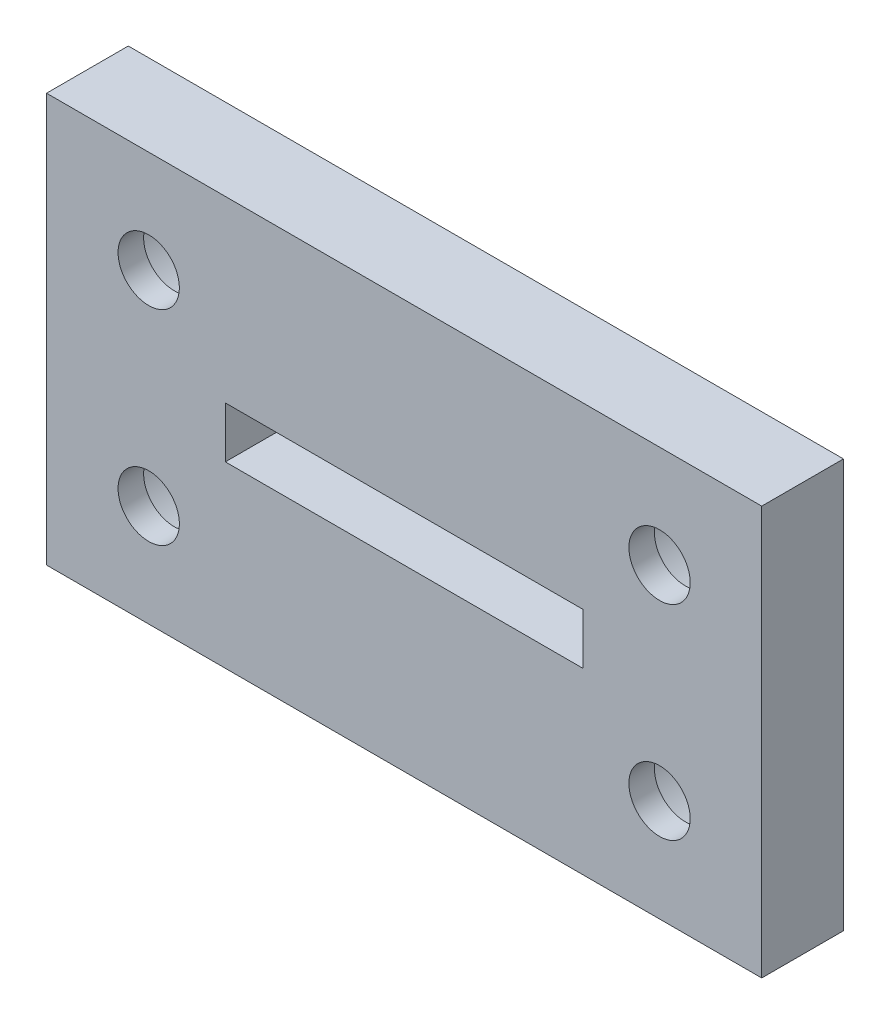
SolidWorks part; units mm, degrees
ref_plane "Front Plane" through (0, 0, 0) normal (0, 0, 1) x (1, 0, 0)
ref_plane "Top Plane" through (0, 0, 0) normal (0, 1, 0) x (1, 0, 0)
ref_plane "Right Plane" through (0, 0, 0) normal (1, 0, 0) x (0, 0, -1)
sketch "Sketch1" plane through (0, 0, 0) normal (0, 0, 1) x (1, 0, 0)
  line L0 (7, 9) -> (21, 9)
  line L1 (0, 0) -> (28, 0)
  line L2 (0, 0) -> (0, 16)
  line L3 (0, 16) -> (28, 16)
  line L4 (28, 0) -> (28, 16)
  line L5 (21, 7) -> (21, 9)
  line L6 (7, 7) -> (21, 7)
  line L7 (7, 7) -> (7, 9)
  line L8 (14, 17.5004) -> (14, -9.815) construction
  line L9 (-1.5747, 8) -> (30.0341, 8) construction
  circle A0 centre (4, 12) radius 1.2
  circle A1 centre (4, 4) radius 1.2
  circle A2 centre (24, 4) radius 1.2
  circle A3 centre (24, 12) radius 1.2
  dimension "D4" = 2.4
  dimension "D1" = 28
  dimension "D2" = 16
  dimension "D5" = 4
  dimension "D6" = 4
  dimension "D7" = 14
  dimension "D9" = 8
  dimension "D3" = 7
extrude "Boss-Extrude1" add sketch "Sketch1" along normal blind 3.2
sketch "Sketch2" plane through (0, 0, 0) normal (0, 0, -1) x (-1, 0, 0)
  circle A0 centre (-4, 12) radius 3
  circle A1 centre (-4, 4) radius 3
  circle A2 centre (-24, 4) radius 3
  circle A3 centre (-24, 12) radius 3
extrude "Cut-Extrude1" cut sketch "Sketch2" against normal blind 2.2
